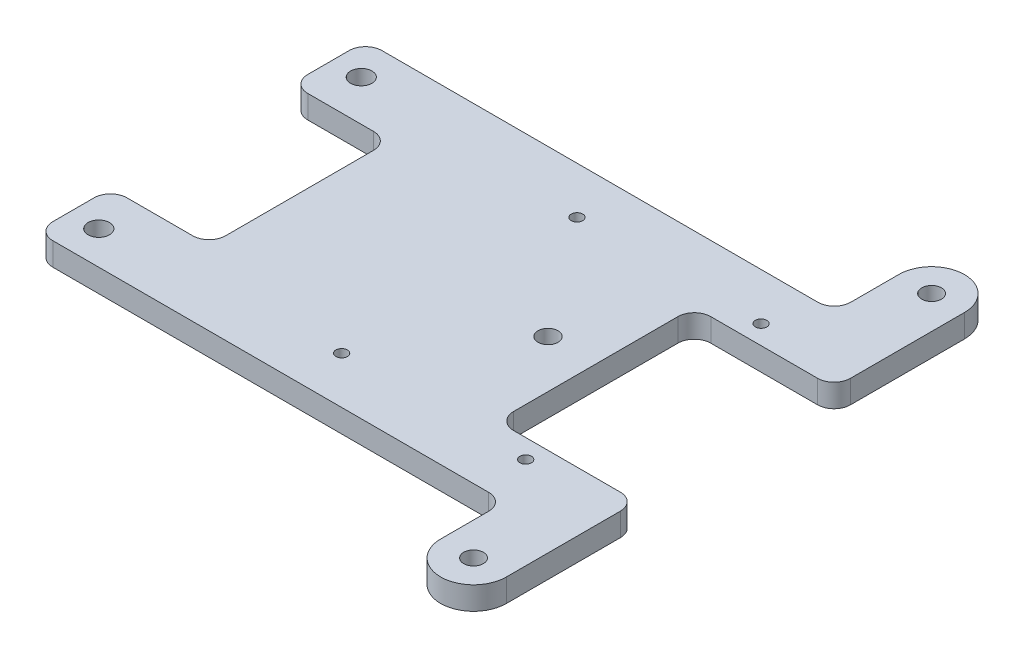
SolidWorks part; units mm, degrees
ref_plane "Alzado" through (0, 0, 0) normal (0, 0, 1) x (1, 0, 0)
ref_plane "Planta" through (0, 0, 0) normal (0, 1, 0) x (1, 0, 0)
ref_plane "Vista lateral" through (0, 0, 0) normal (1, 0, 0) x (0, 0, -1)
sketch "Croquis2" plane through (0, 8, 0) normal (0, 1, 0) x (1, 0, 0)
  line L0 (162.6, -69.675) -> (162.6, 69.675) construction
  line L1 (0, -50.075) -> (8.85, -50.075) construction
  line L2 (8.85, 50.075) -> (0, 50.075) construction
  line L3 (0, 50.075) -> (0, -50.075) construction
  line L4 (162.6, -69.675) -> (162.6, 69.675)
  line L5 (0, -50.075) -> (8.85, -50.075)
  line L6 (8.85, 50.075) -> (0, 50.075)
  line L7 (0, 50.075) -> (0, -50.075)
  line L8 (8.85, 50.075) -> (142.6, 50.075)
  line L9 (142.6, 69.675) -> (142.6, 50.075)
  line L13 (142.6, -69.675) -> (142.6, -50.075)
  line L15 (8.85, -50.075) -> (142.6, -50.075)
  arc A0 (162.6, 69.675) -> (142.6, 69.675) centre (152.6, 69.675) ccw construction
  arc A1 (142.6, -69.675) -> (162.6, -69.675) centre (152.6, -69.675) ccw construction
  arc A2 (162.6, 69.675) -> (142.6, 69.675) centre (152.6, 69.675) ccw
  arc A3 (142.6, -69.675) -> (162.6, -69.675) centre (152.6, -69.675) ccw
  circle A4 centre (152.6, -69.675) radius 3 construction
  circle A5 centre (8.85, -39.925) radius 3.25 construction
  circle A6 centre (8.85, 39.925) radius 3.25 construction
  circle A7 centre (152.6, 69.675) radius 3 construction
  circle A8 centre (152.6, -69.675) radius 3
  circle A9 centre (8.85, -39.925) radius 3.25
  circle A10 centre (8.85, 39.925) radius 3.25
  circle A11 centre (152.6, 69.675) radius 3
extrude "Saliente-Extruir1" add sketch "Croquis2" along normal blind 7
sketch "Croquis3" plane through (0, 15, 0) normal (0, 1, 0) x (1, 0, 0)
  arc A0 (105.6, -2.5527) -> (105.6, 2.5527) centre (105.6, 0) ccw construction
  arc A1 (105.6, 2.5527) -> (105.6, -2.5527) centre (105.6, 0) ccw construction
  arc A2 (78.6, -34.55) -> (78.6, -37.05) centre (78.6, -35.8) ccw construction
  arc A3 (78.6, -37.05) -> (78.6, -34.55) centre (78.6, -35.8) ccw construction
  arc A4 (134.6, -34.55) -> (134.6, -37.05) centre (134.6, -35.8) ccw construction
  arc A5 (134.6, -37.05) -> (134.6, -34.55) centre (134.6, -35.8) ccw construction
  arc A6 (134.6, 34.55) -> (134.6, 37.05) centre (134.6, 35.8) ccw construction
  arc A7 (134.6, 37.05) -> (134.6, 34.55) centre (134.6, 35.8) ccw construction
  arc A8 (78.6, 37.05) -> (78.6, 34.55) centre (78.6, 35.8) ccw construction
  arc A9 (78.6, 34.55) -> (78.6, 37.05) centre (78.6, 35.8) ccw construction
  arc A10 (105.6, -2.5527) -> (105.6, 2.5527) centre (105.6, 0) ccw construction
  arc A11 (105.6, 2.5527) -> (105.6, -2.5527) centre (105.6, 0) ccw construction
  arc A12 (78.6, -34.55) -> (78.6, -37.05) centre (78.6, -35.8) ccw construction
  arc A13 (78.6, -37.05) -> (78.6, -34.55) centre (78.6, -35.8) ccw construction
  arc A14 (134.6, -34.55) -> (134.6, -37.05) centre (134.6, -35.8) ccw construction
  arc A15 (134.6, -37.05) -> (134.6, -34.55) centre (134.6, -35.8) ccw construction
  arc A16 (134.6, 34.55) -> (134.6, 37.05) centre (134.6, 35.8) ccw construction
  arc A17 (134.6, 37.05) -> (134.6, 34.55) centre (134.6, 35.8) ccw construction
  arc A18 (78.6, 37.05) -> (78.6, 34.55) centre (78.6, 35.8) ccw construction
  arc A19 (78.6, 34.55) -> (78.6, 37.05) centre (78.6, 35.8) ccw construction
  arc A20 (134.6, 34.05) -> (134.6, 37.55) centre (134.6, 35.8) ccw
  arc A21 (134.6, 37.55) -> (134.6, 34.05) centre (134.6, 35.8) ccw
  arc A22 (78.6, 34.05) -> (78.6, 37.55) centre (78.6, 35.8) ccw
  arc A23 (78.6, 37.55) -> (78.6, 34.05) centre (78.6, 35.8) ccw
  arc A24 (134.6, -34.05) -> (134.6, -37.55) centre (134.6, -35.8) ccw
  arc A25 (134.6, -37.55) -> (134.6, -34.05) centre (134.6, -35.8) ccw
  arc A26 (78.6, -37.55) -> (78.6, -34.05) centre (78.6, -35.8) ccw
  arc A27 (78.6, -34.05) -> (78.6, -37.55) centre (78.6, -35.8) ccw
  arc A28 (105.6, -3.0527) -> (105.6, 3.0527) centre (105.6, 0) ccw
  arc A29 (105.6, 3.0527) -> (105.6, -3.0527) centre (105.6, 0) ccw
  dimension "D1" = 0.5
  dimension "D2" = 0.5
extrude "Cortar-Extruir3" cut sketch "Croquis3" against normal blind 7
sketch "Croquis4" plane through (0, 15, 0) normal (0, 1, 0) x (1, 0, 0)
  line L0 (-30, -27.5) -> (-30, 27.5)
  line L1 (-30, -27.5) -> (30, -27.5)
  line L2 (-30, 27.5) -> (30, 27.5)
  line L3 (30, -27.5) -> (30, 27.5)
  line L4 (-30, -27.5) -> (30, 27.5) construction
  line L5 (-30, 27.5) -> (30, -27.5) construction
  point P1 (0, 0)
  dimension "D1" = 60
  dimension "D2" = 55
extrude "Cortar-Extruir4" cut sketch "Croquis4" against normal blind 7
fillet "Redondeo1" radius 5 8 edges at (0, 11.5, 50.075) (142.6, 11.5, 50.075) (142.6, 11.5, -50.075) (0, 11.5, -50.075) (0, 11.5, 27.5) (30, 11.5, 27.5) (30, 11.5, -27.5) (0, 11.5, -27.5)
sketch "Croquis5" plane through (0, 15, 0) normal (0, 1, 0) x (1, 0, 0)
  line L0 (125.1, -30) -> (205.1, -30)
  line L1 (120.1, -25) -> (120.1, 25)
  line L2 (205.1, -30) -> (205.1, 30)
  line L3 (125.1, 30) -> (205.1, 30)
  line L4 (120.1, -30) -> (205.1, 30) construction
  line L5 (205.1, -30) -> (120.1, 30) construction
  line L6 (162.6, -69.675) -> (162.6, 69.675) construction
  arc A0 (120.1, -25) -> (125.1, -30) centre (125.1, -25) ccw
  arc A1 (120.1, 25) -> (125.1, 30) centre (125.1, 25) cw
  point P1 (162.6, 0)
  point P8 (162.6, 0)
  dimension "D3" = 5
  dimension "D1" = 60
  dimension "D2" = 85
extrude "Cortar-Extruir5" cut sketch "Croquis5" against normal blind 10
fillet "Redondeo2" radius 5 2 edges at (162.6, 11.5, -30) (162.6, 11.5, 30)
